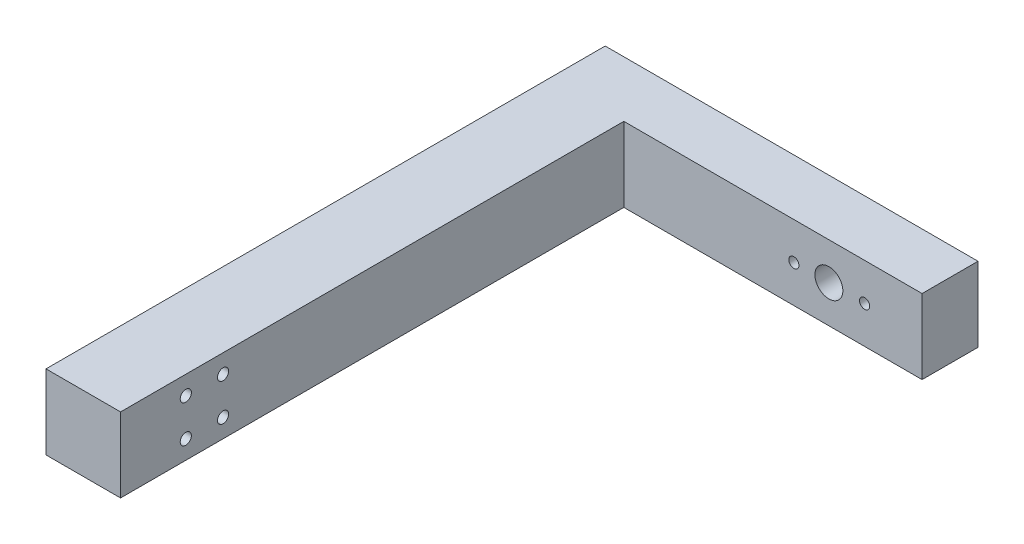
SolidWorks part; units mm, degrees
ref_plane "Front Plane" through (0, 0, 0) normal (0, 0, 1) x (1, 0, 0)
ref_plane "Top Plane" through (0, 0, 0) normal (0, 1, 0) x (1, 0, 0)
ref_plane "Right Plane" through (0, 0, 0) normal (1, 0, 0) x (0, 0, -1)
sketch "Sketch2" plane through (0, 0, 0) normal (0, 1, 0) x (1, 0, 0)
  line L0 (-59.7087, 220.3398) -> (140.2913, 220.3398)
  line L1 (140.2913, 220.3398) -> (140.2913, 190.3398)
  line L2 (140.2913, 190.3398) -> (-19.7087, 190.3398)
  line L3 (-19.7087, 190.3398) -> (-19.7087, -79.6602)
  line L4 (-19.7087, -79.6602) -> (-59.7087, -79.6602)
  line L5 (-59.7087, -79.6602) -> (-59.7087, 220.3398)
  dimension "D1" = 30
  dimension "D2" = 200
  dimension "D3" = 300
  dimension "D4" = 40
extrude "Boss-Extrude2" add sketch "Sketch2" along normal blind 40
sketch "Sketch3" plane through (0, 0, 0) normal (1, 0, 0) x (0, 0, -1)
  line L0 (-79.6602, 20) -> (237.9306, 20) construction
  line L1 (205.3398, 40) -> (205.3398, 0) construction
  line L2 (190.3398, 40) -> (220.3398, 40) construction
  line L3 (190.3398, 0) -> (220.3398, 0) construction
  line L4 (-79.6602, 40) -> (-79.6602, 0) construction
  line L6 (-79.6602, 40) -> (190.3398, 40) construction
  circle A0 centre (-24.6602, 30) radius 3
  circle A1 centre (-44.6602, 30) radius 3
  dimension "D2" = 6
  dimension "D4" = 6
  dimension "D1" = 55
  dimension "D3" = 20
  dimension "D5" = 10
extrude "Cut-Extrude1" cut sketch "Sketch3" against normal through all
sketch "Sketch4" plane through (-19.7087, 0, 0) normal (1, 0, 0) x (0, 0, -1)
  line L0 (-79.6602, 0) -> (190.3398, 0) construction
  line L1 (-79.6602, 40) -> (-79.6602, 0) construction
  circle A0 centre (-44.6602, 10) radius 3
  circle A1 centre (-24.6602, 10) radius 3
  dimension "D1" = 6
  dimension "D4" = 6
  dimension "D2" = 10
  dimension "D3" = 35
  dimension "D5" = 20
extrude "Cut-Extrude2" cut sketch "Sketch4" against normal blind 40
sketch "Sketch5" plane through (0, 0, -220.3398) normal (0, 0, -1) x (-1, 0, 0)
  line L0 (59.7087, 40) -> (59.7087, 0) construction
  line L1 (-140.2913, 40) -> (59.7087, 40) construction
  circle A0 centre (-90.2913, 20) radius 7.5
  dimension "D3" = 15
  dimension "D1" = 150
  dimension "D2" = 20
extrude "Cut-Extrude3" cut sketch "Sketch5" against normal blind 40
sketch "Sketch6" plane through (0, 0, -220.3398) normal (0, 0, -1) x (-1, 0, 0)
  line L0 (-90.4796, 19.8213) -> (-90.4796, 41.8967) construction
  line L1 (-90.4796, 41.8967) -> (-90.4796, -1.6359) construction
  line L2 (-140.2913, 20) -> (85.0186, 20) construction
  line L3 (-140.2913, 40) -> (-140.2913, 0) construction
  circle A0 centre (-109.4654, 20) radius 2.7358
  circle A1 centre (-71.4938, 20) radius 2.7358
  dimension "D1" = 18.9858
extrude "Cut-Extrude4" cut sketch "Sketch6" against normal blind 40
